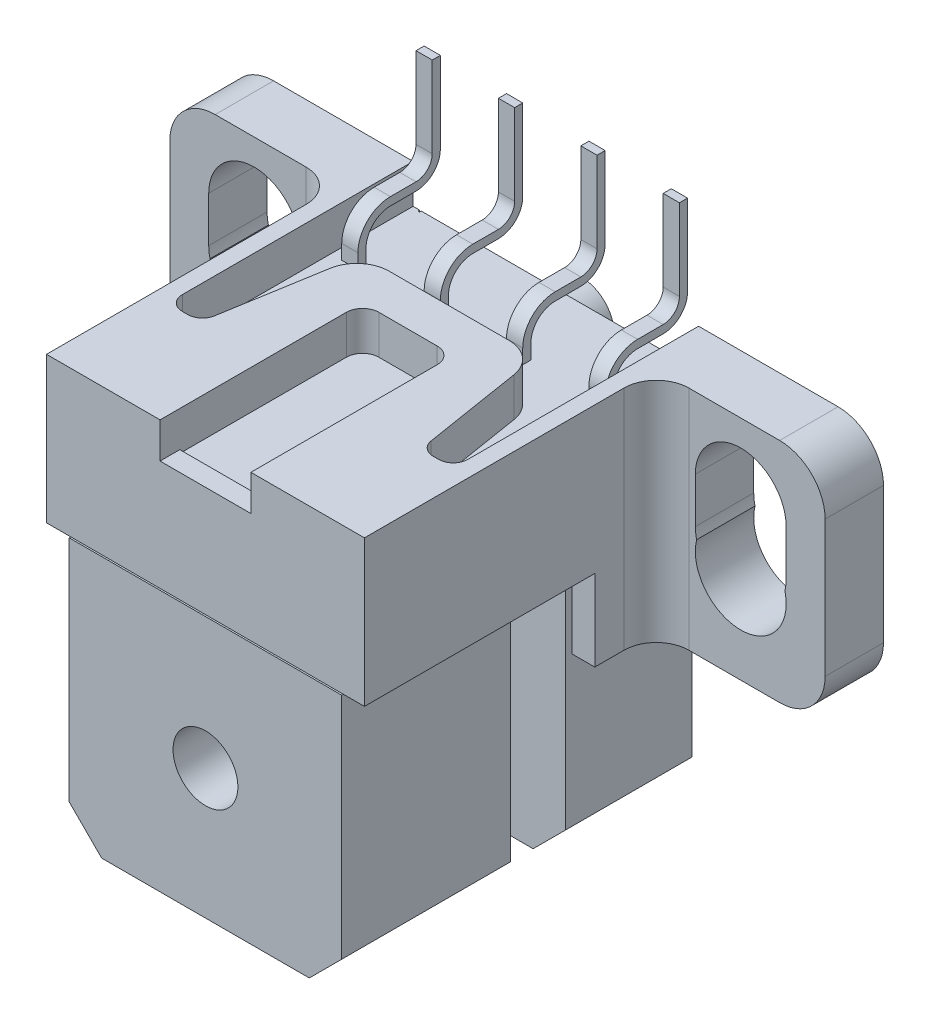
SolidWorks part; units mm, degrees
ref_plane "Спереди" through (0, 0, 0) normal (0, 0, 1) x (1, 0, 0)
ref_plane "Сверху" through (0, 0, 0) normal (0, 1, 0) x (1, 0, 0)
ref_plane "Справа" through (0, 0, 0) normal (1, 0, 0) x (0, 0, -1)
sketch "Эскиз1" plane through (0, 0, 0) normal (0, 0, 1) x (1, 0, 0)
  line L0 (7.4, 0) -> (8.4, 1)
  line L1 (1, 0) -> (7.4, 0)
  line L2 (0, 1) -> (0, 12.6)
  line L3 (0, 12.6) -> (8.4, 12.6)
  line L4 (8.4, 1) -> (8.4, 12.6)
  line L5 (0, 1) -> (1, 0)
  point P0 (0, 0)
  point P3 (8.4, 0)
  dimension "D1" = 12.6
  dimension "D2" = 8.4
extrude "Бобышка-Вытянуть1" add sketch "Эскиз1" along normal blind 10.8
sketch "Эскиз2" plane through (0, 0, 0) normal (0, 0, -1) x (-1, 0, 0)
  line L0 (-8.4, 12.6) -> (0, 12.6) construction
  circle A0 centre (-4.2, 10.3) radius 1
  circle A1 centre (-4.2, 3.9) radius 1
  dimension "D2" = 6.4
  dimension "D3" = 2
  dimension "D1" = 8.7
extrude "Бобышка-Вытянуть2" add sketch "Эскиз2" along normal blind 0.8
sketch "Эскиз3" plane through (8.4, 0, 0) normal (1, 0, 0) x (0, 0, -1)
  line L0 (-10.8, 0) -> (0, 0) construction
  line L1 (-3.9, 0) -> (-5.6, 0)
  line L2 (-3.9, 0) -> (-3.9, 8.1)
  line L3 (-3.9, 8.1) -> (-5.6, 8.1)
  line L4 (-5.6, 0) -> (-5.6, 8.1)
  line L5 (0, 12.6) -> (0, 1) construction
  line L6 (0.8, 2.9) -> (0.8, 4.9) construction
  line L7 (0.8, 3.9) -> (-1.4983, 3.9) construction
  dimension "D1" = 3.9
  dimension "D2" = 1.7
  dimension "D3" = 4.2
extrude "Вырез-Вытянуть1" cut sketch "Эскиз3" against normal blind 17.8
sketch "Эскиз4" plane through (0, 12.6, 0) normal (0, 1, 0) x (1, 0, 0)
  line L0 (9.1, -10.8) -> (-0.7, -10.8)
  line L1 (14.3, 0) -> (-5.9, 0)
  line L3 (8.4, 0) -> (0, 0) construction
  line L4 (14.3, 0) -> (14.3, -1.8)
  line L5 (14.3, -1.8) -> (10.1, -1.8)
  line L6 (9.1, -2.8) -> (9.1, -10.8)
  line L7 (-0.7, -10.8) -> (-0.7, -2.8)
  line L8 (-1.7, -1.8) -> (-5.9, -1.8)
  line L9 (-5.9, -1.8) -> (-5.9, 0)
  arc A0 (-0.7, -2.8) -> (-1.7, -1.8) centre (-1.7, -2.8) ccw
  arc A1 (10.1, -1.8) -> (9.1, -2.8) centre (10.1, -2.8) ccw
  point P5 (4.2, -10.8)
  point P9 (4.2, 0)
  dimension "D5" = 1
  dimension "D1" = 9.8
  dimension "D2" = 20.2
  dimension "D3" = 1.8
  dimension "D4" = 1.8
extrude "Бобышка-Вытянуть3" add sketch "Эскиз4" against normal up to vertex
sketch "Эскиз5" plane through (0, 0, 10.8) normal (0, 0, 1) x (1, 0, 0)
  line L0 (0, 8.1) -> (0, 1) construction
  line L1 (8.4, 8.1) -> (0, 8.1)
  line L2 (8.4, 8.1) -> (8.4, 8.05)
  line L3 (8.4, 8.05) -> (0, 8.05)
  line L4 (0, 8.1) -> (0, 8.05)
extrude "Вырез-Вытянуть2" cut sketch "Эскиз5" against normal blind 1
sketch "Эскиз6" plane through (0, 0, 10.8) normal (0, 0, 1) x (1, 0, 0)
  line L0 (1, 0) -> (7.4, 0) construction
  circle A0 centre (4.2, 4) radius 1
  dimension "D1" = 4
  dimension "D2" = 2
extrude "Вырез-Вытянуть3" cut sketch "Эскиз6" against normal blind 8
sketch "Эскиз7" plane through (0, 12.6, 0) normal (0, 1, 0) x (1, 0, 0)
  line L0 (8.6, 0) -> (8.6, -7.1124)
  line L1 (14.3, 0) -> (-5.9, 0) construction
  line L2 (8.15, -7.5624) -> (7.9834, -7.5624)
  line L3 (7.5391, -7.1839) -> (7.0497, -4.1412)
  line L4 (6.0624, -3.3) -> (2.3617, -3.3)
  line L5 (1.3755, -4.1344) -> (0.863, -7.1869)
  line L6 (0.4192, -7.5624) -> (0.25, -7.5624)
  line L7 (-0.2, -7.1124) -> (-0.2, 0)
  line L8 (9.1, -10.8) -> (9.1, -2.8) construction
  line L9 (-0.7, -2.8) -> (-0.7, -10.8) construction
  line L10 (8.6, 0) -> (-0.2, 0)
  line L11 (4.2, -10.8) -> (5.6, -10.8)
  line L12 (9.1, -10.8) -> (-0.7, -10.8) construction
  line L13 (5.6, -10.8) -> (5.6, -5.0564)
  line L14 (5.1, -4.5564) -> (3.3, -4.5564)
  line L15 (2.8, -5.0564) -> (2.8, -10.8)
  line L16 (2.8, -10.8) -> (4.2, -10.8)
  arc A0 (2.3617, -3.3) -> (1.3755, -4.1344) centre (2.3617, -4.3) ccw
  arc A1 (7.0497, -4.1412) -> (6.0624, -3.3) centre (6.0624, -4.3) ccw
  arc A2 (0.25, -7.5624) -> (-0.2, -7.1124) centre (0.25, -7.1124) cw
  arc A3 (0.863, -7.1869) -> (0.4192, -7.5624) centre (0.4192, -7.1124) cw
  arc A4 (7.9834, -7.5624) -> (7.5391, -7.1839) centre (7.9834, -7.1124) cw
  arc A5 (8.6, -7.1124) -> (8.15, -7.5624) centre (8.15, -7.1124) cw
  arc A6 (3.3, -4.5564) -> (2.8, -5.0564) centre (3.3, -5.0564) ccw
  arc A7 (5.6, -5.0564) -> (5.1, -4.5564) centre (5.1, -5.0564) ccw
  point P23 (-0.2, -7.5624)
  point P26 (0.8, -7.5624)
  point P29 (7.6, -7.5624)
  point P32 (8.6, -7.5624)
  dimension "D6" = 1
  dimension "D7" = 0.45
  dimension "D8" = 0.5
  dimension "D1" = 0.5
  dimension "D2" = 0.5
  dimension "D3" = 1
  dimension "D4" = 1
  dimension "D5" = 3.3
extrude "Вырез-Вытянуть4" cut sketch "Эскиз7" against normal blind 1.2
sketch "Эскиз8" plane through (0, 11.4, 0) normal (0, 1, 0) x (1, 0, 0)
  line L0 (2.8, -5.0564) -> (2.8, -10.8) construction
  line L1 (5.6, -10.8) -> (2.8, -10.8)
  line L2 (5.6, -10.8) -> (5.6, -10.1916)
  line L3 (5.6, -10.1916) -> (2.8, -10.1916)
  line L4 (2.8, -10.8) -> (2.8, -10.1916)
extrude "Бобышка-Вытянуть4" add sketch "Эскиз8" along normal blind 0.1
sketch "Эскиз9" plane through (0, 8.1, 0) normal (0, -1, 0) x (1, 0, 0)
  line L0 (0, 0) -> (0, 3.7)
  line L1 (0, 0) -> (0, 3.9) construction
  line L2 (0, 3.7) -> (-0.7, 3.7)
  line L3 (-0.7, 2.8) -> (-0.7, 10.8) construction
  line L4 (-0.7, 3.7) -> (-0.7, 2.8)
  line L5 (-1.7, 1.8) -> (-5.9, 1.8)
  line L6 (-5.9, 1.8) -> (-5.9, 0)
  line L7 (-5.9, 0) -> (0, 0)
  line L8 (14.3, 0) -> (8.4, 0)
  line L9 (8.4, 0) -> (8.4, 3.7)
  line L10 (8.4, 3.9) -> (8.4, 0) construction
  line L11 (8.4, 3.7) -> (9.1, 3.7)
  line L12 (9.1, 10.8) -> (9.1, 2.8) construction
  line L13 (9.1, 3.7) -> (9.1, 2.8)
  line L14 (1, 3.9) -> (0, 3.9) construction
  line L15 (10.1, 1.8) -> (14.3, 1.8)
  line L16 (14.3, 1.8) -> (14.3, 0)
  line L17 (0, 3.9) -> (8.4, 3.9) construction
  arc A0 (9.1, 2.8) -> (10.1, 1.8) centre (10.1, 2.8) ccw
  arc A1 (-0.7, 2.8) -> (-1.7, 1.8) centre (-1.7, 2.8) cw
  dimension "D1" = 0.2
  dimension "D2" = 0.2
extrude "Бобышка-Вытянуть5" add sketch "Эскиз9" along normal blind 2.5
sketch "Эскиз10" plane through (0, 8.1, 0) normal (0, -1, 0) x (1, 0, 0)
  line L1 (0, 3.9) -> (8.4, 3.9)
  line L2 (0, 3.9) -> (0, 5.6)
  line L3 (0, 5.6) -> (8.4, 5.6)
  line L4 (8.4, 3.9) -> (8.4, 5.6)
extrude "Вырез-Вытянуть5" cut sketch "Эскиз10" against normal blind 0.05
fillet "Скругление1" radius 1.4 4 edges at (-5.9, 5.6, 0.9) (-5.9, 12.6, 0.9) (14.3, 12.6, 0.9) (14.3, 5.6, 0.9)
sketch "Эскиз11" plane through (0, 0, 0) normal (0, 0, -1) x (-1, 0, 0)
  line L0 (-8.6, 11.4) -> (0.2, 11.4) construction
  line L1 (-8.4, 5.5617) -> (-8.35, 5.5617)
  line L2 (-8.4, 5.5617) -> (-8.4, 11.4)
  line L3 (-8.4, 11.4) -> (-8.35, 11.4)
  line L4 (-8.35, 5.5617) -> (-8.35, 11.4)
  line L6 (0, 5.5712) -> (-0.05, 5.5712)
  line L7 (0, 5.5712) -> (0, 11.4)
  line L8 (0, 11.4) -> (-0.05, 11.4)
  line L9 (-0.05, 5.5712) -> (-0.05, 11.4)
extrude "Вырез-Вытянуть8" cut sketch "Эскиз11" against normal blind 0.05 contours L9 L8 L7 L6 | L4 L3 L2 L1
sketch "Эскиз12" plane through (0, 0, 0) normal (0, 0, -1) x (-1, 0, 0)
  line L0 (3.3, 9) -> (3.3, 10.4) construction
  line L1 (1.9, 9) -> (1.9, 10.4)
  line L2 (4.7, 9) -> (4.7, 10.4)
  line L3 (-11.7, 10.4) -> (-11.7, 9) construction
  line L4 (-10.3, 10.4) -> (-10.3, 9)
  line L5 (-13.1, 10.4) -> (-13.1, 9)
  circle A0 centre (-4.2, 4) radius 1 construction
  arc A1 (-10.3, 10.4) -> (-13.1, 10.4) centre (-11.7, 10.4) ccw
  arc A2 (-13.0606, 8.67) -> (-10.3394, 8.67) centre (-11.7, 8.34) ccw
  arc A3 (-10.3394, 8.67) -> (-10.3, 9) centre (-11.7, 9) ccw
  arc A4 (1.9, 9) -> (1.9394, 8.67) centre (3.3, 9) ccw
  arc A5 (4.7, 10.4) -> (1.9, 10.4) centre (3.3, 10.4) ccw
  arc A6 (-13.1, 9) -> (-13.0606, 8.67) centre (-11.7, 9) ccw
  arc A7 (1.9394, 8.67) -> (4.6606, 8.67) centre (3.3, 8.34) ccw
  circle A8 centre (-4.2, 4) radius 1 construction
  arc A9 (4.6606, 8.67) -> (4.7, 9) centre (3.3, 9) ccw
  point P5 (-11.7, 9.7)
  point P10 (3.3, 9.7)
  dimension "D1" = 7.5
  dimension "D3" = 1.4
  dimension "D5" = 5
  dimension "D2" = 7.5
  dimension "D4" = 1.4
  dimension "D6" = 5
  dimension "D7" = 4.34
  dimension "D8" = 4.34
extrude "Вырез-Вытянуть9" cut sketch "Эскиз12" against normal blind 4
sketch "Эскиз13" plane through (0, 11.4, 0) normal (0, 1, 0) x (1, 0, 0)
  line L5 (5.72, -2.54) -> (5.22, -2.54)
  line L6 (5.72, -2.54) -> (5.72, 3)
  line L7 (5.72, 3) -> (5.22, 3)
  line L8 (5.22, -2.54) -> (5.22, 3)
  line L9 (8.26, -2.54) -> (7.76, -2.54)
  line L10 (8.26, -2.54) -> (8.26, 3)
  line L11 (8.26, 3) -> (7.76, 3)
  line L12 (7.76, -2.54) -> (7.76, 3)
  line L13 (3.18, -2.54) -> (2.68, -2.54)
  line L14 (3.18, -2.54) -> (3.18, 3)
  line L15 (3.18, 3) -> (2.68, 3)
  line L16 (2.68, -2.54) -> (2.68, 3)
  line L17 (5.72, -2.54) -> (5.22, -2.54)
  line L18 (5.72, -2.54) -> (5.72, 3)
  line L19 (5.72, 3) -> (5.22, 3)
  line L20 (5.22, -2.54) -> (5.22, 3)
  line L21 (0.64, -2.54) -> (0.14, -2.54)
  line L22 (0.64, -2.54) -> (0.64, 3)
  line L23 (0.64, 3) -> (0.14, 3)
  line L24 (0.14, -2.54) -> (0.14, 3)
extrude "Бобышка-Вытянуть6" add sketch "Эскиз13" along normal blind 1.45 contours L5 L8 L7 L6 | L13 L16 L15 L14 | L21 L24 L23 L22 | L9 L12 L11 L10
fillet "Скругление2" radius 1 4 edges at (0.39, 12.85, 2.54) (2.93, 12.85, 2.54) (5.47, 12.85, 2.54) (8.01, 12.85, 2.54)
sketch "Эскиз14" plane through (0.14, 0, 0) normal (-1, 0, 0) x (0, 0, 1)
  line L0 (-3, 12.6) -> (1.54, 12.6)
  line L1 (-3, 12.85) -> (-3, 11.4) construction
  line L2 (2.29, 11.85) -> (2.29, 11.4)
  line L3 (0, 11.4) -> (7.1124, 11.4) construction
  line L4 (2.29, 11.4) -> (-3, 11.4)
  line L5 (-3, 11.4) -> (-3, 12.6)
  line L6 (1.54, 12.85) -> (-3, 12.85) construction
  line L7 (2.54, 11.85) -> (2.54, 11.4) construction
  arc A0 (1.54, 12.6) -> (2.29, 11.85) centre (1.54, 11.85) cw
  dimension "D3" = 0.75
  dimension "D1" = 0.25
  dimension "D2" = 0.25
extrude "Вырез-Вытянуть10" cut sketch "Эскиз14" against normal up to vertex
sketch "Эскиз15" plane through (8.26, 0, 0) normal (1, 0, 0) x (0, 0, -1)
  line L0 (-1.54, 12.85) -> (3, 12.85) construction
  line L1 (0, 12.85) -> (3, 12.85)
  line L2 (0, 12.85) -> (0, 12.6)
  line L3 (0, 12.6) -> (3, 12.6)
  line L4 (3, 12.85) -> (3, 12.6)
extrude "Вырез-Вытянуть11" cut sketch "Эскиз15" against normal up to vertex
sketch "Эскиз16" plane through (0, 12.85, 0) normal (0, 1, 0) x (1, 0, 0)
  line L0 (8.26, -1.54) -> (8.26, 0) construction
  line L1 (7.76, 0) -> (8.26, 0)
  line L2 (7.76, 0) -> (7.76, -0.25)
  line L3 (7.76, -0.25) -> (8.26, -0.25)
  line L4 (8.26, 0) -> (8.26, -0.25)
  line L5 (5.72, -1.54) -> (5.72, 0) construction
  line L6 (5.22, 0) -> (5.72, 0)
  line L7 (5.22, 0) -> (5.22, -0.25)
  line L8 (5.22, -0.25) -> (5.72, -0.25)
  line L9 (5.72, 0) -> (5.72, -0.25)
  line L10 (3.18, -1.54) -> (3.18, 0) construction
  line L11 (2.68, 0) -> (3.18, 0)
  line L12 (2.68, 0) -> (2.68, -0.25)
  line L13 (2.68, -0.25) -> (3.18, -0.25)
  line L14 (3.18, 0) -> (3.18, -0.25)
  line L15 (0.64, -1.54) -> (0.64, 0) construction
  line L16 (0.14, 0) -> (0.64, 0)
  line L17 (0.14, 0) -> (0.14, -0.25)
  line L18 (0.14, -0.25) -> (0.64, -0.25)
  line L19 (0.64, 0) -> (0.64, -0.25)
  dimension "D1" = 0.25
  dimension "D2" = 0.25
extrude "Бобышка-Вытянуть7" add sketch "Эскиз16" along normal blind 3
fillet "Скругление3" radius 0.5 4 edges at (0.39, 12.85, 0.25) (2.93, 12.85, 0.25) (5.47, 12.85, 0.25) (8.01, 12.85, 0.25)
fillet "Скругление4" radius 0.75 4 edges at (8.01, 12.6, 0) (5.47, 12.6, 0) (0.39, 12.6, 0) (2.93, 12.6, 0)
